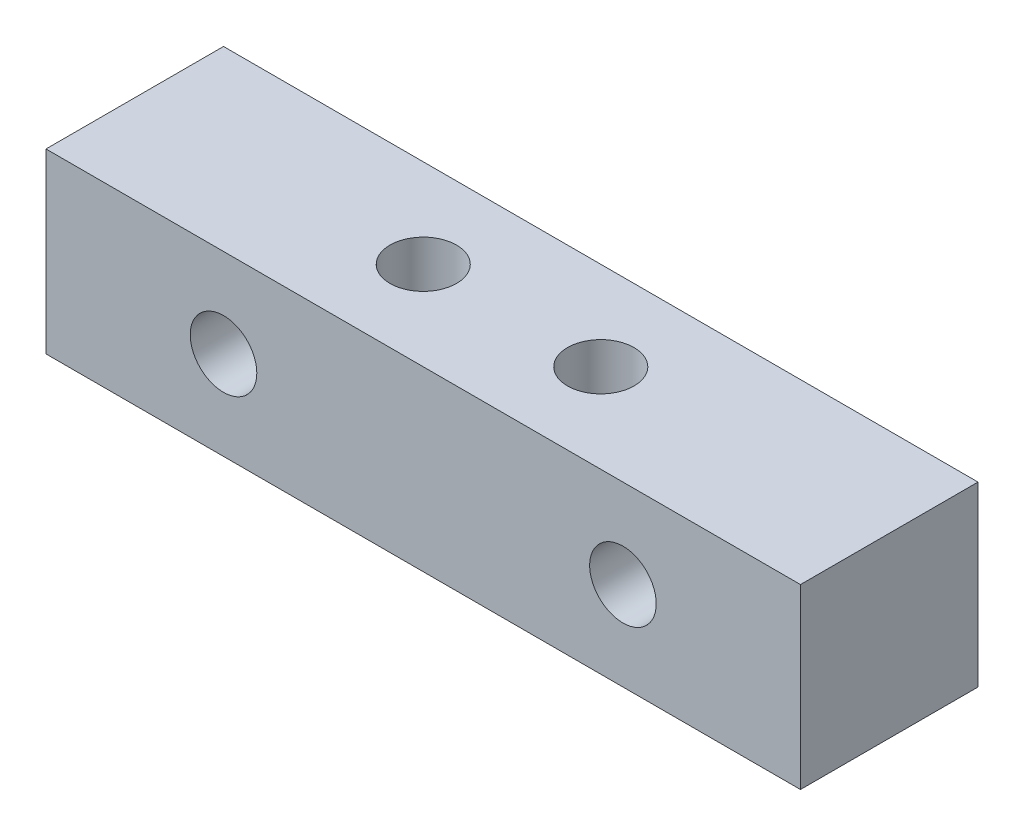
SolidWorks part; units mm, degrees
ref_plane "前视基准面" through (0, 0, 0) normal (0, 0, 1) x (1, 0, 0)
ref_plane "上视基准面" through (0, 0, 0) normal (0, 1, 0) x (1, 0, 0)
ref_plane "右视基准面" through (0, 0, 0) normal (1, 0, 0) x (0, 0, -1)
other "Configuration Table"
sketch "草图1" plane through (0, 0, 0) normal (0, 0, 1) x (1, 0, 0)
  line L1 (0, 0) -> (34, 0)
  line L2 (0, 0) -> (0, 8)
  line L3 (0, 8) -> (34, 8)
  line L4 (34, 0) -> (34, 8)
  dimension "D1" = 34
  dimension "D2" = 8
extrude "凸台-拉伸1" add sketch "草图1" along normal blind 8
sketch "草图2" plane through (0, 0, 8) normal (0, 0, 1) x (1, 0, 0)
  line L0 (0, 4) -> (34, 4) construction
  line L1 (0, 8) -> (0, 0) construction
  line L2 (34, 0) -> (34, 8) construction
  circle A0 centre (8, 4) radius 1.5
  circle A1 centre (26, 4) radius 1.5
  dimension "D1" = 3
  dimension "D2" = 3
  dimension "D4" = 8
  dimension "D3" = 18
extrude "切除-拉伸1" cut sketch "草图2" against normal through all
sketch "草图3" plane through (0, 8, 0) normal (0, 1, 0) x (1, 0, 0)
  line L0 (0, -4) -> (34, -4) construction
  line L1 (0, -8) -> (0, 0) construction
  line L2 (34, -8) -> (34, 0) construction
  circle A0 centre (13, -4) radius 1.5
  circle A1 centre (21, -4) radius 1.5
  dimension "D1" = 3
  dimension "D2" = 3
  dimension "D3" = 8
  dimension "D4" = 13
extrude "切除-拉伸2" cut sketch "草图3" against normal through all
